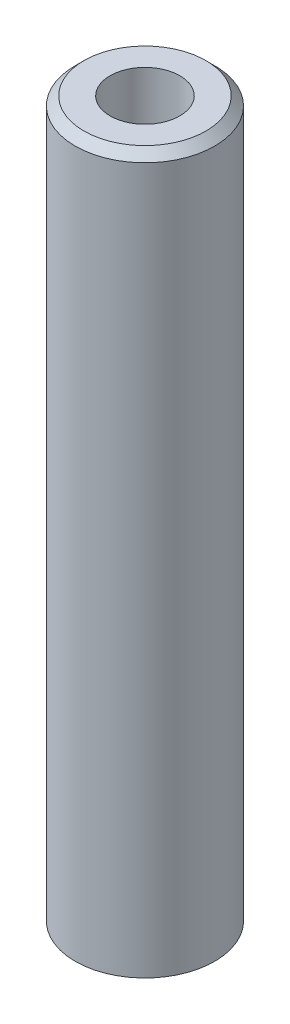
SolidWorks part; units mm, degrees
ref_plane "Front Plane" through (0, 0, 0) normal (0, 0, 1) x (1, 0, 0)
ref_plane "Top Plane" through (0, 0, 0) normal (0, 1, 0) x (1, 0, 0)
ref_plane "Right Plane" through (0, 0, 0) normal (1, 0, 0) x (0, 0, -1)
sketch "Sketch1" plane through (0, 0, 0) normal (0, 1, 0) x (1, 0, 0)
  circle A0 centre (0, 0) radius 2
  circle A1 centre (0, 0) radius 4
  dimension "D1" = 4
  dimension "D2" = 2
extrude "Boss-Extrude1" add sketch "Sketch1" along normal blind 41
chamfer "Chamfer1" distance 0.5 angle 45 1 edges at (0, 41, 4)
